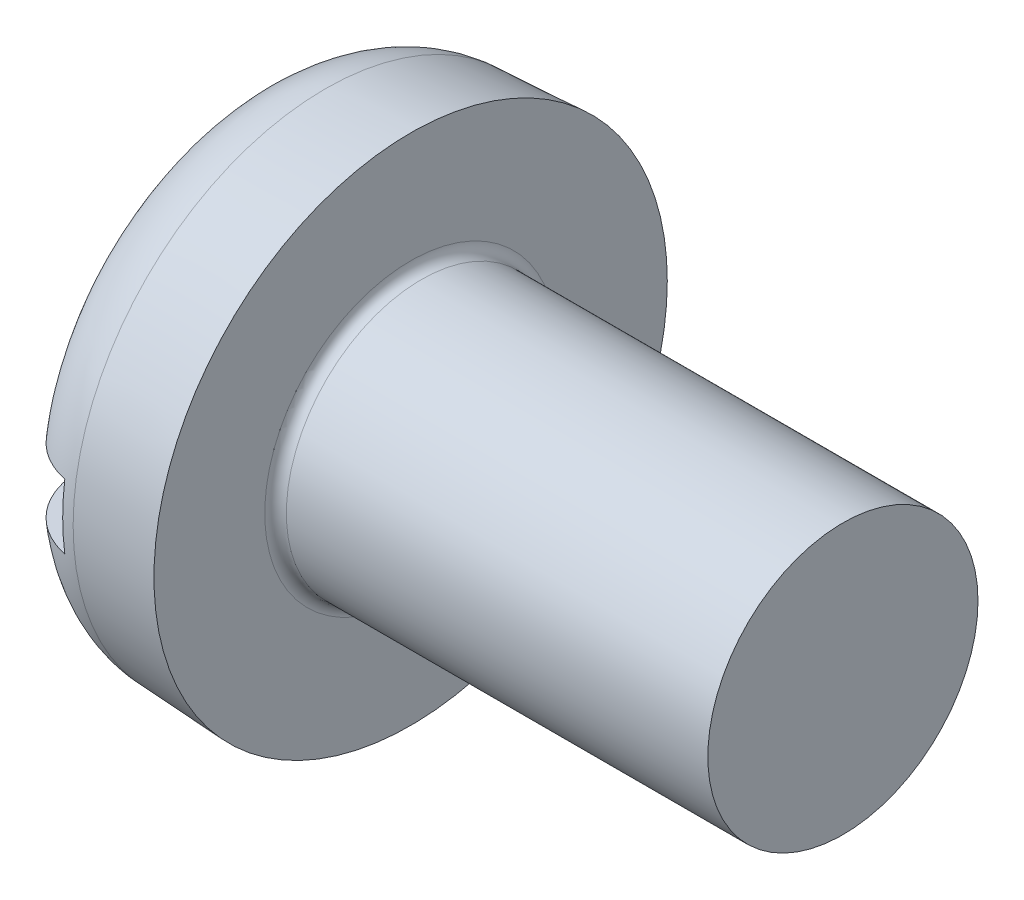
SolidWorks part; units mm, degrees
ref_plane "Front" through (0, 0, 0) normal (0, 0, 1) x (1, 0, 0)
ref_plane "Top" through (0, 0, 0) normal (0, 1, 0) x (1, 0, 0)
ref_plane "Right" through (0, 0, 0) normal (1, 0, 0) x (0, 0, -1)
ref_plane "Plane1" through (3, 0, 0) normal (1, 0, 0) x (0, 0, -1)
sketch "Sketch1" plane through (3, 0, 0) normal (1, 0, 0) x (0, 0, -1)
  circle A0 centre (0, 0) radius 4.75
  dimension "dk" = 9.5
extrude "BaseHead" add sketch "Sketch1" against normal blind 3 draft 3
sketch "Sketch2" plane through (3, 0, 0) normal (1, 0, 0) x (0, 0, -1)
  line L0 (0, 0) -> (1.6, 0) construction
  circle A0 centre (0, 0) radius 2.5
  dimension "d" = 5
  dimension "a" = 1.6
extrude "BaseBody" add sketch "Sketch2" along normal blind 8
cosmetic thread "ThreadCosmetic1" [suppressed] parameters "D1"=8, "D2"=4.134
fillet "HeadFillet2" radius 1.5 1 edges at (0, 0, -4.5928)
sketch "Sketch3" plane through (1.05, -1.05, 0) normal (0, 0, 1) x (0, -1, 0)
  line L1 (-1.65, 0.15) -> (-0.45, 0.15)
  line L2 (-1.65, 0.15) -> (-1.65, -1.05)
  line L3 (-1.65, -1.05) -> (-0.45, -1.05)
  line L4 (-0.45, 0.15) -> (-0.45, -1.05)
  line L5 (-4.2193, -1.05) -> (2.1193, -1.05) construction
  dimension "n" = 1.2
  dimension "t" = 1.2
  dimension "m" = 0.6
extrude "Notch" cut sketch "Sketch3" against normal through all and the other way through all
fillet "HeadFillet1" radius 0.2 1 edges at (3, 0, -2.5)
sketch "Sketch4" plane through (0, 0, 0) normal (0, 0, 1) x (1, 0, 0)
  line L0 (-27, 7.067) -> (-27, 2.5)
  line L1 (3, 7.067) -> (-27, 7.067)
  line L2 (3, 7.067) -> (3, 2.067)
  line L3 (3, 2.067) -> (-29, 2.067)
  line L6 (6.4188, 0) -> (-0.5067, 0) construction
  line L8 (11, -2.5) -> (11, 2.5) construction
  line L9 (-27, 2.5) -> (-29, 2.067)
  line L11 (3, -4.75) -> (3, 4.75) construction
  line L12 (11, 2.5) -> (3.2, 2.5) construction
  dimension "dd" = 5
  dimension "b1" = 4.134
  dimension "b" = 38
  dimension "x" = 2
sketch "Sketch5" plane through (0, 0, 0) normal (0, 0, 1) x (1, 0, 0)
  line L0 (11, 2.125) -> (11.2165, 2.5)
  line L1 (11.2165, 2.5) -> (11.2165, 2.933)
  line L2 (11.2165, 2.933) -> (10.7835, 2.933)
  line L3 (10.7835, 2.933) -> (10.7835, 2.5)
  line L4 (10.7835, 2.5) -> (11, 2.125)
  line L5 (0, 0) -> (4.296, 0) construction
  line L6 (11, -2.5) -> (11, 2.5) construction
  dimension "D1" = 5
  dimension "D2" = 0.433
revolve "Cut-Revolve10" [suppressed] cut sketch "Sketch5" angle 360 about L5
pattern_linear "LPattern10" [suppressed] count 15 spacing 0.5196 along (1, 0, 0)
scale "缩放比例1" scale about origin uniform scaling yes scale factor 0.25
equation "\"m@Sketch3\" = \"n@Sketch3\" / 2"
equation "\"D1@Plane1\" = \"k@BaseHead\""
equation "\"D1@Sketch5\" = \"d@Sketch2\""
equation "\"D2@Sketch5\" =  ( \"d@Sketch2\" - \"D2@ThreadCosmetic1\" )  / 2"
equation "\"D3@LPattern10\" = \"D2@Sketch5\" * 1.2"
equation "\"D1@LPattern10\" = \"D1@ThreadCosmetic1\" / \"D3@LPattern10\" "
